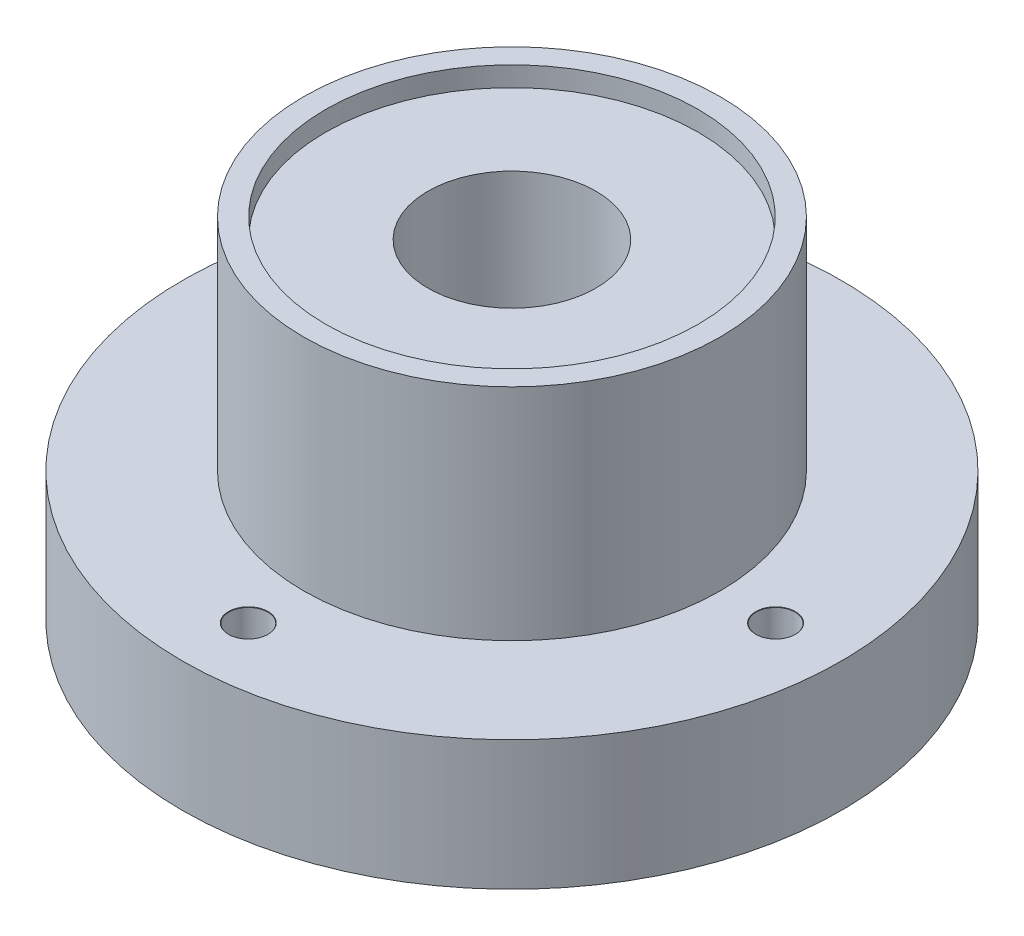
SolidWorks part; units mm, degrees
material "Ceramic Porcelain"
ref_plane "Front Plane" through (0, 0, 0) normal (0, 0, 1) x (1, 0, 0)
ref_plane "Top Plane" through (0, 0, 0) normal (0, 1, 0) x (1, 0, 0)
ref_plane "Right Plane" through (0, 0, 0) normal (1, 0, 0) x (0, 0, -1)
sketch "Sketch1" plane through (0, 0, 0) normal (0, 1, 0) x (1, 0, 0)
  circle A0 centre (0, 0) radius 25.4
extrude "Boss-Extrude1" add sketch "Sketch1" along normal blind 25.4
sketch "Sketch2" plane through (0, 25.4, 0) normal (0, 1, 0) x (1, 0, 0)
  circle A0 centre (0, 0) radius 16.05
extrude "Cut-Extrude1" cut sketch "Sketch2" against normal blind 15.422 flip side to cut
sketch "Sketch3" plane through (0, 0, 0) normal (0, -1, 0) x (1, 0, 0)
  circle A0 centre (0, 0) radius 6.477
extrude "Cut-Extrude2" cut sketch "Sketch3" against normal through all
sketch "Sketch4" plane through (0, 25.4, 0) normal (0, 1, 0) x (1, 0, 0)
  circle A0 centre (0, 0) radius 14.351
  circle A1 centre (0, 0) radius 16.05 construction
  circle A2 centre (0, 0) radius 16.05
extrude "Boss-Extrude2" add sketch "Sketch4" along normal blind 1.524
sketch "Sketch6" plane through (0, 9.978, 0) normal (0, 1, 0) x (1, 0, 0)
  circle A0 centre (0, 0) radius 25.4 construction
  circle A1 centre (0, 0) radius 16.05 construction
  circle A2 centre (0, 0) radius 25.4
  circle A3 centre (0, 0) radius 16.05
  point P0 (0, 20.32)
  dimension "D2" = 20.32
  dimension "D1" = 0
hole_wizard "Ø3.0mm Dowel Hole1" positions "3DSketch2" profile "Sketch8" hole size "Ø3.0" standard "ANSI Metric" end condition through all
sketch3d "3DSketch2"
  point P0 (0, 9.978, -20.32)
sketch "Sketch8" plane through (0, 9.978, -20.32) normal (1, 0, 0) x (0, 0, 1)
  line L0 (0, 0) -> (0, 9.978)
  line L1 (0, 9.978) -> (1.5, 9.978)
  line L2 (1.5, 9.978) -> (1.5, 0.025)
  line L3 (1.5, 0.025) -> (1.525, 0)
  line L5 (1.525, 0) -> (0, 0)
  line L6 (-1.5, 0.025) -> (-1.525, 0) construction
  line L11 (0, -6.35) -> (0, 107.95) construction
  dimension "Thru Hole Dia." = 3
  dimension "Thru Hole Depth" = 9.978
  dimension "Near C'Sink Dia." = 3.05
  dimension "Near C'Sink Angle" = 90
pattern_circular "CirPattern1" count 4 over 360 about axis through (0, 0, 0) along (0, 1, 0) of "Ø3.0mm Dowel Hole1"
